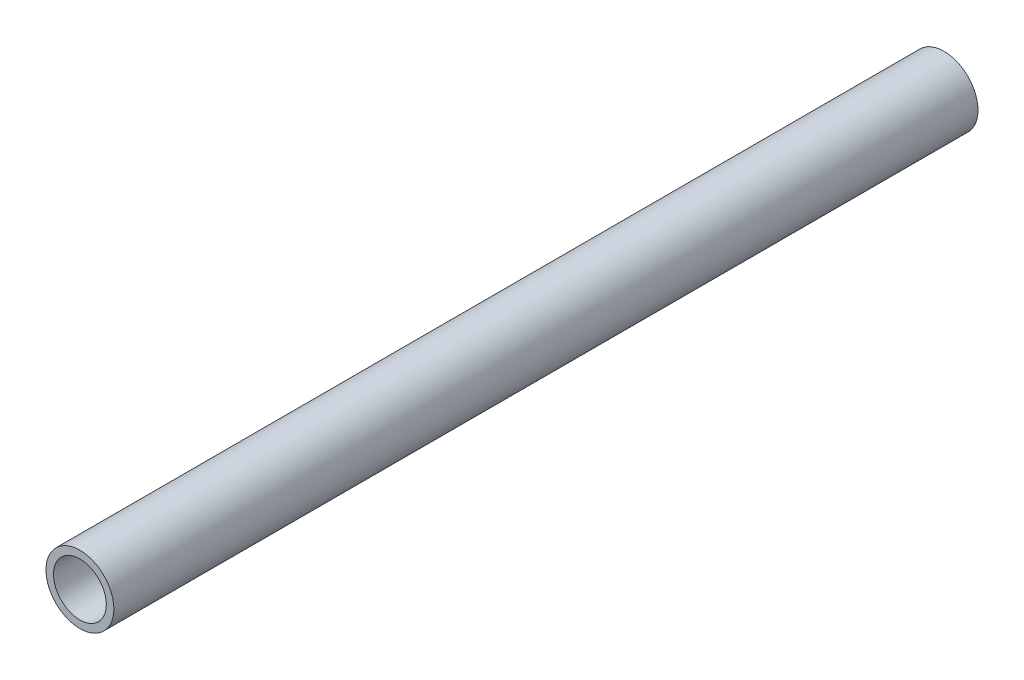
SolidWorks part; units mm, degrees
ref_plane "Front Plane" through (0, 0, 0) normal (0, 0, 1) x (1, 0, 0)
ref_plane "Top Plane" through (0, 0, 0) normal (0, 1, 0) x (1, 0, 0)
ref_plane "Right Plane" through (0, 0, 0) normal (1, 0, 0) x (0, 0, -1)
sketch "Sketch1" plane through (0, 0, 0) normal (0, 0, 1) x (1, 0, 0)
  circle A0 centre (0, 0) radius 7
  circle A1 centre (0, 0) radius 9
  dimension "D1" = 14
  dimension "D2" = 18
extrude "Boss-Extrude1" add sketch "Sketch1" along normal blind 229.04
